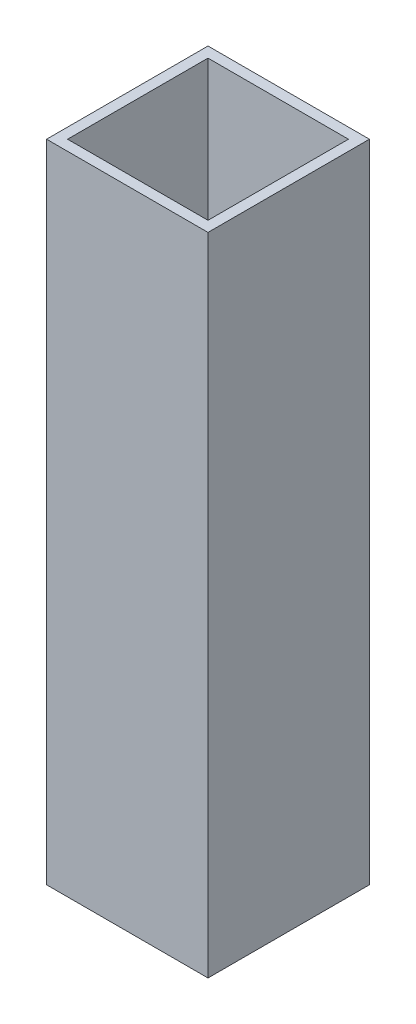
SolidWorks part; units mm, degrees
ref_plane "Front Plane" through (0, 0, 0) normal (0, 0, 1) x (1, 0, 0)
ref_plane "Top Plane" through (0, 0, 0) normal (0, 1, 0) x (1, 0, 0)
ref_plane "Right Plane" through (0, 0, 0) normal (1, 0, 0) x (0, 0, -1)
sketch "Sketch1" plane through (0, 0, 0) normal (0, 1, 0) x (1, 0, 0)
  line L1 (0, 0) -> (25.4, 0)
  line L2 (0, 0) -> (0, -25.4)
  line L3 (0, -25.4) -> (25.4, -25.4)
  line L4 (25.4, 0) -> (25.4, -25.4)
extrude "Boss-Extrude1" add sketch "Sketch1" along normal blind 101.6
sketch "Sketch2" plane through (0, 101.6, 0) normal (0, 1, 0) x (1, 0, 0)
  line L0 (25.4, 0) -> (0, 0) construction
  line L1 (1.651, -1.651) -> (23.749, -1.651)
  line L2 (1.651, -1.651) -> (1.651, -23.749)
  line L3 (1.651, -23.749) -> (23.749, -23.749)
  line L4 (23.749, -1.651) -> (23.749, -23.749)
  line L5 (0, 0) -> (0, -25.4) construction
  line L6 (0, -25.4) -> (25.4, -25.4) construction
  line L7 (25.4, -25.4) -> (25.4, 0) construction
  point P6 (12.7, 0)
  dimension "D1" = 1.651
  dimension "D2" = 1.651
  dimension "D3" = 1.651
  dimension "D4" = 1.651
extrude "Cut-Extrude1" cut sketch "Sketch2" against normal blind 101.6
